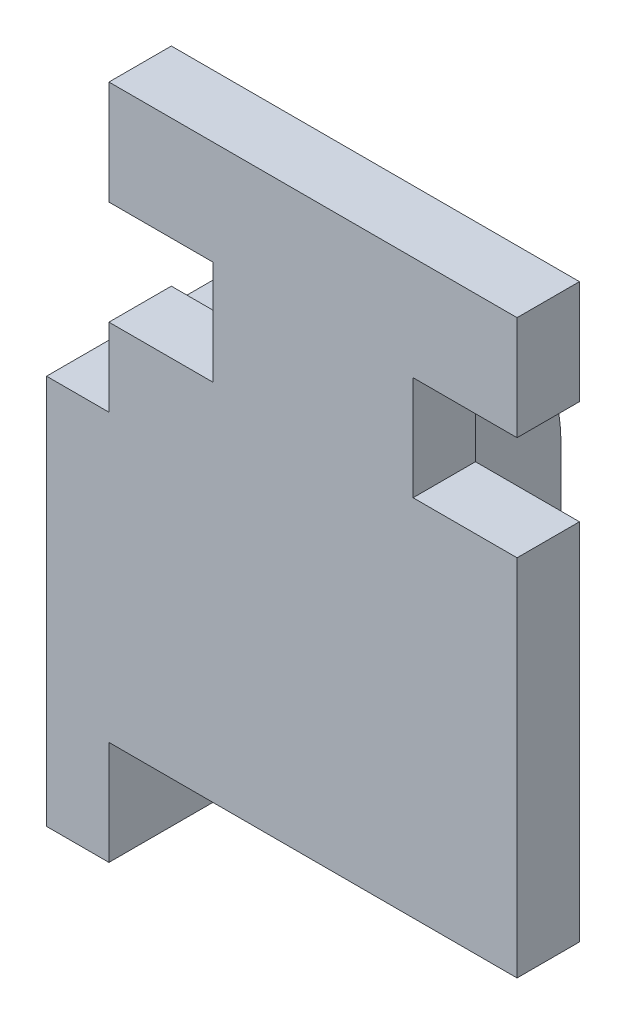
SolidWorks part; units mm, degrees
material "PBT General Purpose"
ref_plane "Front Plane" through (0, 0, 0) normal (0, 0, 1) x (1, 0, 0)
ref_plane "Top Plane" through (0, 0, 0) normal (0, 1, 0) x (1, 0, 0)
ref_plane "Right Plane" through (0, 0, 0) normal (1, 0, 0) x (0, 0, -1)
sketch "Sketch1" plane through (0, 0, 0) normal (0, 0, 1) x (1, 0, 0)
  line L0 (0, 0) -> (0, 1.4)
  line L1 (0, 1.4) -> (0.4, 1.4)
  line L2 (0.4, 1.4) -> (0.4, 1.8)
  line L3 (0.4, 1.8) -> (0, 1.8)
  line L4 (0, 1.8) -> (0, 2.2)
  line L5 (0, 2.2) -> (1.57, 2.2)
  line L6 (1.57, 2.2) -> (1.57, 1.8)
  line L7 (1.57, 1.8) -> (1.17, 1.8)
  line L8 (1.17, 1.8) -> (1.17, 1.4)
  line L9 (1.17, 1.4) -> (1.57, 1.4)
  line L10 (1.57, 1.4) -> (1.57, 0)
  line L11 (1.57, 0) -> (0, 0)
  dimension "D1" = 0.4
  dimension "D2" = 0.4
  dimension "D3" = 0.77
  dimension "D4" = 0.4
  dimension "D5" = 0.4
  dimension "D6" = 1.4
  dimension "D7" = 0.4
extrude "Boss-Extrude1" add sketch "Sketch1" along normal blind 0.24
sketch "Sketch2" plane through (0, 0, 0) normal (-1, 0, 0) x (0, 0, 1)
  line L0 (0.24, 0) -> (0.24, -0.4)
  line L2 (-1.5, -0.4) -> (0.24, -0.4)
  line L3 (-1.5, -0.4) -> (-1.5, 1.1)
  line L4 (-1.5, 1.1) -> (0, 1.1)
  line L5 (0, 1.4) -> (0, 0) construction
  line L6 (0, 1.1) -> (0.24, 1.1)
  line L7 (0.24, 1.4) -> (0.24, 0) construction
  line L8 (0.24, 1.1) -> (0.24, 0)
  line L9 (0.24, 1.4) -> (0, 1.4) construction
  dimension "D1" = 0.3
  dimension "D2" = 1.5
  dimension "D3" = 1.5
extrude "Boss-Extrude2" add sketch "Sketch2" along normal blind 0.24
fillet "Fillet1" radius 1 1 edges at (-0.12, 1.1, -1.5)
